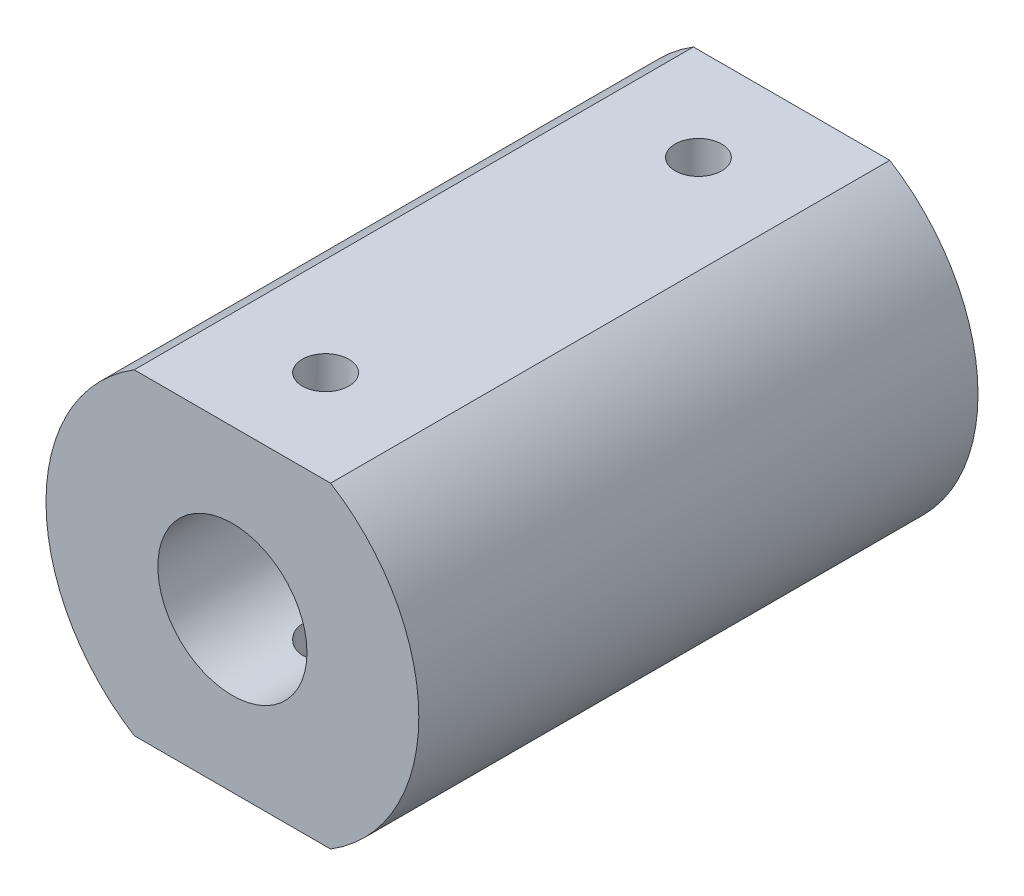
SolidWorks part; units mm, degrees
ref_plane "Plan de face" through (0, 0, 0) normal (0, 0, 1) x (1, 0, 0)
ref_plane "Plan de dessus" through (0, 0, 0) normal (0, 1, 0) x (1, 0, 0)
ref_plane "Plan de droite" through (0, 0, 0) normal (1, 0, 0) x (0, 0, -1)
sketch "Esquisse1" plane through (0, 0, 0) normal (0, 0, 1) x (1, 0, 0)
  circle A0 centre (0, 0) radius 20
  circle A1 centre (0, 0) radius 8
  dimension "D1" = 40
  dimension "D2" = 16
extrude "Boss.-Extru.1" add sketch "Esquisse1" along normal blind 60
sketch "Esquisse2" plane through (0, 0, 60) normal (0, 0, 1) x (1, 0, 0)
  line L1 (-15.2086, 21.8352) -> (24.7914, 21.8352)
  line L2 (-15.2086, 21.8352) -> (-15.2086, 17)
  line L3 (-15.2086, 17) -> (24.7914, 17)
  line L4 (24.7914, 21.8352) -> (24.7914, 17)
  line L5 (-15.2086, 21.8352) -> (24.7914, 17) construction
  line L6 (-15.2086, 17) -> (24.7914, 21.8352) construction
  line L7 (-26.5951, -17) -> (18.0943, -17)
  line L8 (-26.5951, -17) -> (-26.5951, -22.0863)
  line L9 (-26.5951, -22.0863) -> (18.0943, -22.0863)
  line L10 (18.0943, -17) -> (18.0943, -22.0863)
  line L11 (-26.5951, -17) -> (18.0943, -22.0863) construction
  line L12 (-26.5951, -22.0863) -> (18.0943, -17) construction
  circle A0 centre (0, 0) radius 20 construction
  point P0 (4.7914, 19.4176)
  point P7 (-4.2504, -19.5431)
  dimension "D1" = 17
  dimension "D2" = 17
extrude "Enlèv. mat.-Extru.1" cut sketch "Esquisse2" against normal blind 60
sketch "Esquisse3" plane through (0, 17, 0) normal (0, 1, 0) x (1, 0, 0)
  line L0 (-10.5357, 0) -> (10.5357, 0) construction
  line L1 (-10.5357, -60) -> (10.5357, -60) construction
  circle A0 centre (0, -10) radius 2.8699
  circle A1 centre (0, -50) radius 2.8699
  dimension "D1" = 10
  dimension "D2" = 10
hole_wizard "Trou taraudé M61" positions "Esquisse3D1" profile "Esquisse4" tap size "M6" standard "ISO"
sketch3d "Esquisse3D1"
  point P0 (0, 17, 50)
  point P3 (0, 17, 10)
cosmetic thread "Filetage de perçage1" parameters "D1"=9.4007, "D2"=6
cosmetic thread "Filetage de perçage2" parameters "D1"=9.4007, "D2"=6
sketch "Esquisse4" plane through (0, 17, 50) normal (1, 0, 0) x (0, 0, 1)
  line L0 (0, 0) -> (0, 14.5022)
  line L1 (0, 14.5022) -> (2.5, 13)
  line L2 (2.5, 13) -> (2.5, 0)
  line L5 (2.5, 0) -> (0, 0)
  line L10 (0, 14.5022) -> (-2.5, 13) construction
  line L11 (0, -6.35) -> (0, 107.95) construction
  dimension "Diamètre du trou pour taraudage" = 5
  dimension "Profondeur du trou pour taraudage" = 13
  dimension "Angle de pointe" = 118
sketch "Esquisse5" plane through (0, -17, 0) normal (0, -1, 0) x (1, 0, 0)
  line L0 (10.5357, 0) -> (-10.5357, 0) construction
  circle A0 centre (0, 30) radius 2.69
  circle A1 centre (0, 50) radius 2.7038
  dimension "D1" = 20
  dimension "D2" = 30
hole_wizard "Trou taraudé M62" positions "Esquisse3D2" profile "Esquisse6" tap size "M6" standard "ISO"
sketch3d "Esquisse3D2"
  point P0 (0, -17, 50)
  point P3 (0, -17, 30)
sketch "Esquisse6" plane through (0, -17, 50) normal (1, 0, 0) x (0, 0, -1)
  line L0 (0, 0) -> (0, 16.5022)
  line L1 (0, 16.5022) -> (2.5, 15)
  line L2 (2.5, 15) -> (2.5, 0)
  line L5 (2.5, 0) -> (0, 0)
  line L10 (0, 16.5022) -> (-2.5, 15) construction
  line L11 (0, -6.35) -> (0, 107.95) construction
  dimension "Diamètre du trou pour taraudage" = 5
  dimension "Profondeur du trou pour taraudage" = 15
  dimension "Angle de pointe" = 118
cosmetic thread "Filetage de perçage3" parameters "D1"=9.4007, "D2"=6
cosmetic thread "Filetage de perçage4" parameters "D1"=9.4007, "D2"=6
